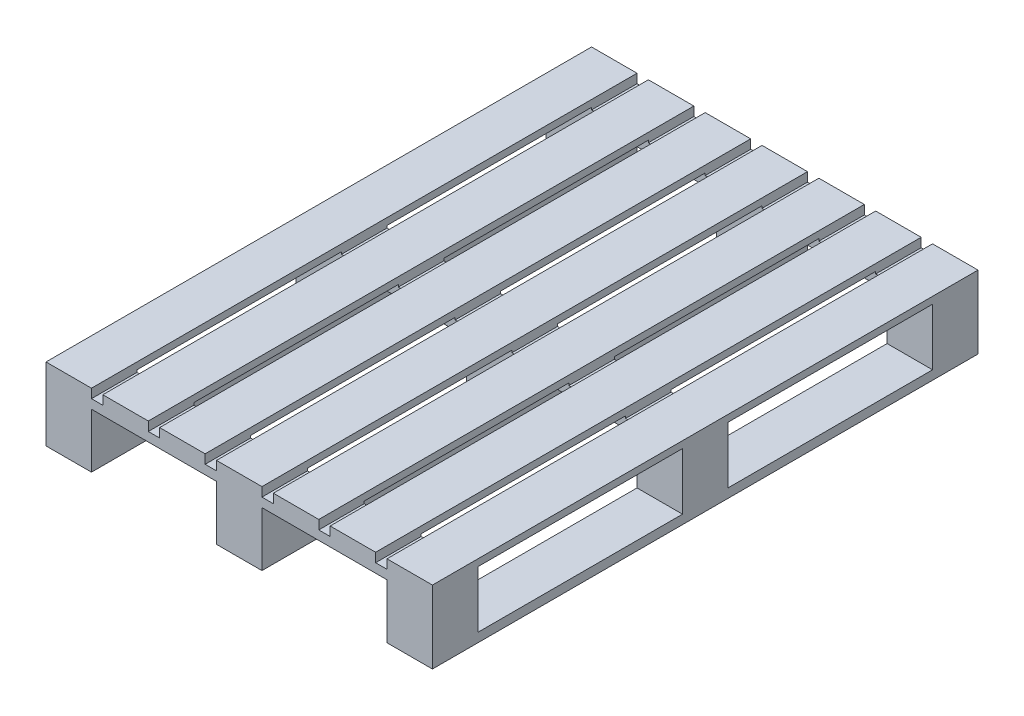
SolidWorks part; units mm, degrees
ref_plane "Front Plane" through (0, 0, 0) normal (0, 0, 1) x (1, 0, 0)
ref_plane "Top Plane" through (0, 0, 0) normal (0, 1, 0) x (1, 0, 0)
ref_plane "Right Plane" through (0, 0, 0) normal (1, 0, 0) x (0, 0, -1)
sketch "Sketch1" plane through (0, 0, 0) normal (0, 0, 1) x (1, 0, 0)
  line L1 (0, 0) -> (850, 0)
  line L2 (0, 0) -> (0, 160)
  line L3 (0, 160) -> (850, 160)
  line L4 (850, 0) -> (850, 160)
  dimension "D1" = 850
  dimension "D2" = 160
extrude "Boss-Extrude1" add sketch "Sketch1" against normal blind 1200
sketch "Sketch2" plane through (0, 0, 0) normal (0, 0, 1) x (1, 0, 0)
  line L0 (0, 0) -> (850, 0) construction
  line L1 (100, 0) -> (375, 0)
  line L2 (100, 0) -> (100, 120)
  line L3 (100, 120) -> (375, 120)
  line L4 (375, 0) -> (375, 120)
  line L5 (0, 160) -> (0, 0) construction
  line L6 (475, 0) -> (750, 0)
  line L7 (475, 0) -> (475, 120)
  line L8 (475, 120) -> (750, 120)
  line L9 (750, 0) -> (750, 120)
  line L11 (850, 0) -> (850, 160) construction
  dimension "D1" = 100
  dimension "D2" = 100
  dimension "D3" = 275
  dimension "D4" = 120
  dimension "D5" = 120
  dimension "D6" = 275
  dimension "D7" = 100
extrude "Cut-Extrude1" cut sketch "Sketch2" against normal through all
sketch "Sketch3" plane through (0, 0, 0) normal (-1, 0, 0) x (0, 0, 1)
  line L1 (-1100, 20) -> (-650, 20)
  line L2 (-1100, 20) -> (-1100, 145)
  line L3 (-1100, 145) -> (-650, 145)
  line L4 (-650, 20) -> (-650, 145)
  line L5 (-550, 20) -> (-100, 20)
  line L6 (-550, 20) -> (-550, 145)
  line L7 (-550, 145) -> (-100, 145)
  line L8 (-100, 20) -> (-100, 145)
  line L9 (-1200, 160) -> (-1200, 0) construction
  line L10 (0, 160) -> (0, 0) construction
  line L11 (-1200, 0) -> (0, 0) construction
  line L12 (-1200, 160) -> (0, 160) construction
  dimension "D1" = 100
  dimension "D2" = 100
  dimension "D3" = 100
  dimension "D4" = 450
  dimension "D5" = 450
  dimension "D6" = 20
  dimension "D7" = 15
  dimension "D8" = 20
  dimension "D9" = 15
extrude "Cut-Extrude2" cut sketch "Sketch3" against normal through all
sketch "Sketch4" plane through (0, 0, 0) normal (0, 0, 1) x (1, 0, 0)
  line L0 (850, 160) -> (0, 160) construction
  line L1 (100, 160) -> (125, 160)
  line L2 (100, 160) -> (100, 140)
  line L3 (100, 140) -> (125, 140)
  line L4 (125, 160) -> (125, 140)
  line L5 (0, 160) -> (0, 0) construction
  line L6 (225, 160) -> (250, 160)
  line L7 (225, 160) -> (225, 140)
  line L8 (225, 140) -> (250, 140)
  line L9 (250, 160) -> (250, 140)
  line L10 (350, 160) -> (375, 160)
  line L11 (350, 160) -> (350, 140)
  line L12 (350, 140) -> (375, 140)
  line L13 (375, 160) -> (375, 140)
  line L14 (475, 160) -> (500, 160)
  line L15 (475, 160) -> (475, 140)
  line L16 (475, 140) -> (500, 140)
  line L17 (500, 160) -> (500, 140)
  line L18 (600, 160) -> (625, 160)
  line L19 (600, 160) -> (600, 140)
  line L20 (600, 140) -> (625, 140)
  line L21 (625, 160) -> (625, 140)
  line L22 (725, 160) -> (750, 160)
  line L23 (725, 160) -> (725, 140)
  line L24 (725, 140) -> (750, 140)
  line L25 (750, 160) -> (750, 140)
  line L26 (850, 0) -> (850, 160) construction
  dimension "D1" = 20
  dimension "D2" = 25
  dimension "D3" = 100
  dimension "D4" = 100
  dimension "D5" = 100
  dimension "D6" = 100
  dimension "D7" = 100
  dimension "D8" = 100
  dimension "D9" = 100
extrude "Cut-Extrude3" cut sketch "Sketch4" against normal through all
